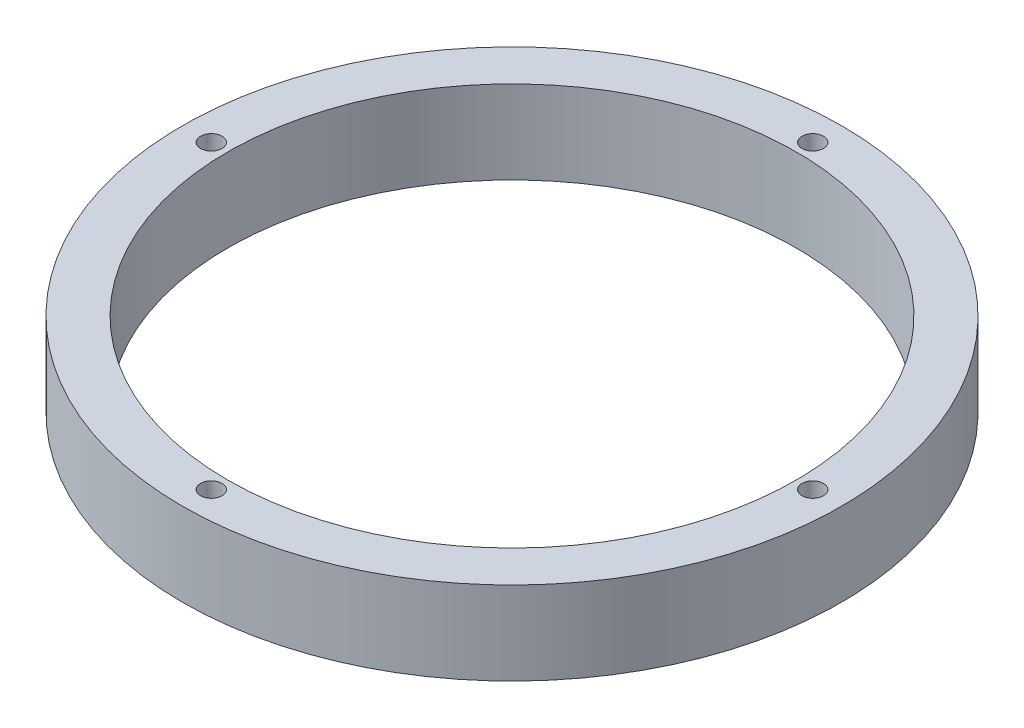
SolidWorks part; units mm, degrees
ref_plane "Front Plane" through (0, 0, 0) normal (0, 0, 1) x (1, 0, 0)
ref_plane "Top Plane" through (0, 0, 0) normal (0, 1, 0) x (1, 0, 0)
ref_plane "Right Plane" through (0, 0, 0) normal (1, 0, 0) x (0, 0, -1)
sketch "Sketch1" plane through (0, 0, 0) normal (0, 1, 0) x (1, 0, 0)
  line L0 (0, 0) -> (0, 73) construction
  line L1 (0, 0) -> (73, 0) construction
  line L2 (0, 0) -> (0, -73) construction
  line L3 (0, 0) -> (-73, 0) construction
  circle A0 centre (0, 0) radius 80
  circle A1 centre (0, 73) radius 2.6
  circle A2 centre (73, 0) radius 2.6
  circle A3 centre (0, -73) radius 2.6
  circle A4 centre (-73, 0) radius 2.6
  circle A5 centre (0, 0) radius 69
  point P14 (0, 0)
  dimension "D1" = 160
  dimension "D2" = 5.2
  dimension "D5" = 138
  dimension "D3" = 73
  dimension "D4" = 4
extrude "Boss-Extrude1" add sketch "Sketch1" along normal blind 20.2
